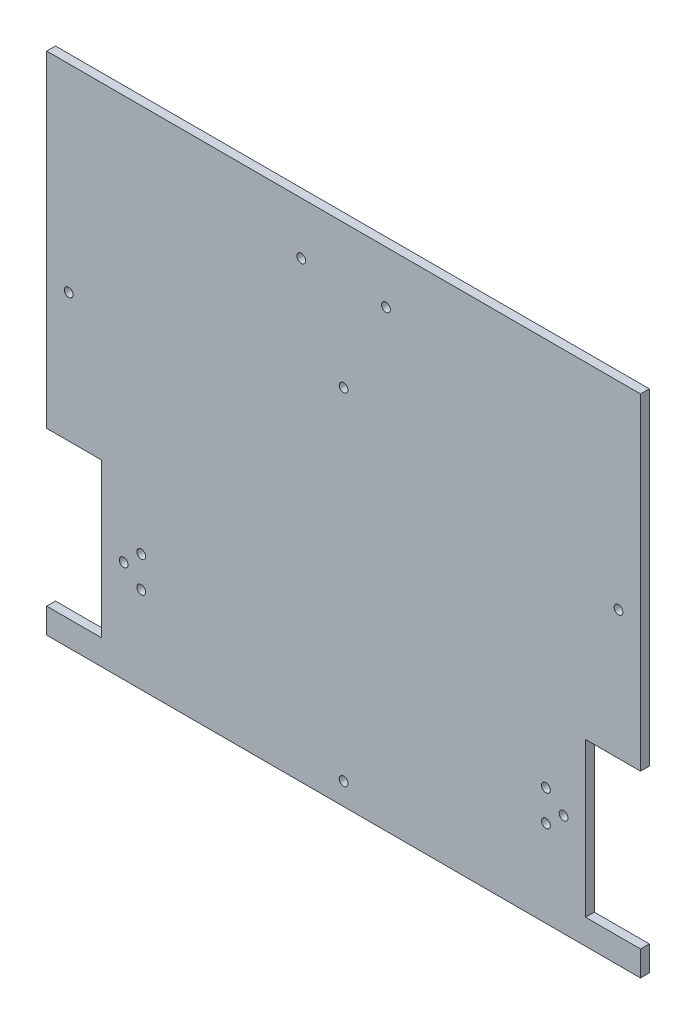
SolidWorks part; units mm, degrees
ref_plane "Front Plane" through (0, 0, 0) normal (0, 0, 1) x (1, 0, 0)
ref_plane "Top Plane" through (0, 0, 0) normal (0, 1, 0) x (1, 0, 0)
ref_plane "Right Plane" through (0, 0, 0) normal (1, 0, 0) x (0, 0, -1)
sketch "Sketch3" plane through (0, 0, 0) normal (0, 0, 1) x (1, 0, 0)
  line L0 (135, 0) -> (135, 230)
  line L1 (135, 230) -> (-135, 230)
  line L2 (-135, 230) -> (-135, 0)
  line L3 (-135, 0) -> (135, 0)
  dimension "D1" = 270
  dimension "D2" = 230
  dimension "D3" = 135
extrude "Boss-Extrude1" add sketch "Sketch3" along normal blind 4
sketch "Sketch4" plane through (0, 0, 4) normal (0, 0, 1) x (1, 0, 0)
  line L0 (-135, 11.4303) -> (-110, 11.4303)
  line L1 (-135, 230) -> (-135, 0) construction
  line L2 (-110, 11.4303) -> (-110, 81.4303)
  line L3 (-110, 81.4303) -> (-135, 81.4303)
  line L4 (-135, 81.4303) -> (-135, 11.4303)
  line L5 (-135, 0) -> (135, 0) construction
  dimension "D1" = 25
  dimension "D2" = 11.4303
  dimension "D3" = 70
extrude "Cut-Extrude1" cut sketch "Sketch4" against normal blind 10
sketch "Sketch6" plane through (0, 0, 4) normal (0, 0, 1) x (1, 0, 0)
  line L0 (-110, 11.4303) -> (162.1189, 11.4303)
  line L1 (135, 11.4303) -> (110, 11.4303)
  line L2 (135, 0) -> (135, 230) construction
  line L3 (110, 11.4303) -> (110, 81.4303)
  line L4 (110, 81.4303) -> (135, 81.4303)
  line L5 (135, 81.4303) -> (135, 11.4303)
  dimension "D1" = 70
  dimension "D2" = 25
extrude "Cut-Extrude2" cut sketch "Sketch6" against normal blind 10 contours L5 L1 L3 L4
sketch "Sketch9" plane through (0, 0, 0) normal (0, 0, -1) x (-1, 0, 0)
  line L0 (110, 11.4303) -> (110, 81.4303) construction
  line L1 (-110, 11.4303) -> (-110, 81.4303) construction
  circle A0 centre (-100, 46.4303) radius 2
  circle A1 centre (100, 46.1864) radius 2
  dimension "D2" = 4
  dimension "D3" = 4
  dimension "D4" = 10
  dimension "D1" = 10
extrude "Cut-Extrude3" cut sketch "Sketch9" against normal blind 10
sketch "Sketch10" plane through (0, 0, 0) normal (0, 0, -1) x (-1, 0, 0)
  line L0 (135, 230) -> (135, 81.4303) construction
  line L1 (-135, 81.4303) -> (-135, 230) construction
  circle A0 centre (-19.25, 206.2683) radius 2
  circle A1 centre (19.25, 206.2683) radius 2
  dimension "D3" = 4
  dimension "D4" = 4
  dimension "D5" = 115.75
  dimension "D1" = 38.5
  dimension "D2" = 115.75
extrude "Cut-Extrude4" cut sketch "Sketch10" against normal blind 10
sketch "Sketch12" plane through (0, 0, 4) normal (0, 0, 1) x (1, 0, 0)
  line L0 (-135, 0) -> (135, 0) construction
  line L1 (-135, 230) -> (-135, 81.4303) construction
  line L2 (135, 81.4303) -> (135, 230) construction
  line L3 (-135, 11.4303) -> (-135, 0) construction
  circle A0 centre (-125, 140) radius 2
  circle A1 centre (125, 140) radius 2
  circle A2 centre (0, 10) radius 2
  circle A3 centre (100, 46.4303) radius 2 construction
  circle A4 centre (-100, 46.1864) radius 2 construction
  dimension "D6" = 4
  dimension "D7" = 4
  dimension "D8" = 4
  dimension "D3" = 10
  dimension "D4" = 10
  dimension "D5" = 135
  dimension "D9" = 10
  dimension "D10" = 200
  dimension "D1" = 140
  dimension "D2" = 140
  dimension "D11" = 270
extrude "Cut-Extrude5" cut sketch "Sketch12" against normal blind 10
sketch "Sketch14" plane through (0, 0, 4) normal (0, 0, 1) x (1, 0, 0)
  line L0 (-135, 230) -> (-135, 81.4303) construction
  circle A0 centre (0, 165) radius 2
  dimension "D2" = 4
  dimension "D1" = 135
extrude "Cut-Extrude7" cut sketch "Sketch14" against normal blind 10
sketch "Sketch15" plane through (0, 0, 4) normal (0, 0, 1) x (1, 0, 0)
  line L0 (0, 10) -> (0, 293.432) construction
  line L2 (-110, 11.4303) -> (-110, 81.4303) construction
  circle A0 centre (92, 53.4303) radius 2
  circle A2 centre (92, 39.4303) radius 2
  circle A4 centre (100, 46.4303) radius 5
  circle A5 centre (-92, 53.1864) radius 2
  circle A6 centre (-92, 39.1864) radius 2
  circle A7 centre (-100, 46.1864) radius 3.8084
  dimension "D5" = 4
  dimension "D6" = 18
  dimension "D7" = 18
  dimension "D8" = 4
  dimension "D14" = 10
  dimension "D2" = 8
  dimension "D11" = 4
  dimension "D12" = 4
  dimension "D3" = 8
  dimension "D4" = 7
  dimension "D9" = 14
  dimension "D10" = 7
  dimension "D13" = 7
extrude "Cut-Extrude8" cut sketch "Sketch15" against normal blind 10
mirror "Mirror1" about plane through (0, 0, 0) normal (1, 0, 0) of "Cut-Extrude8"
